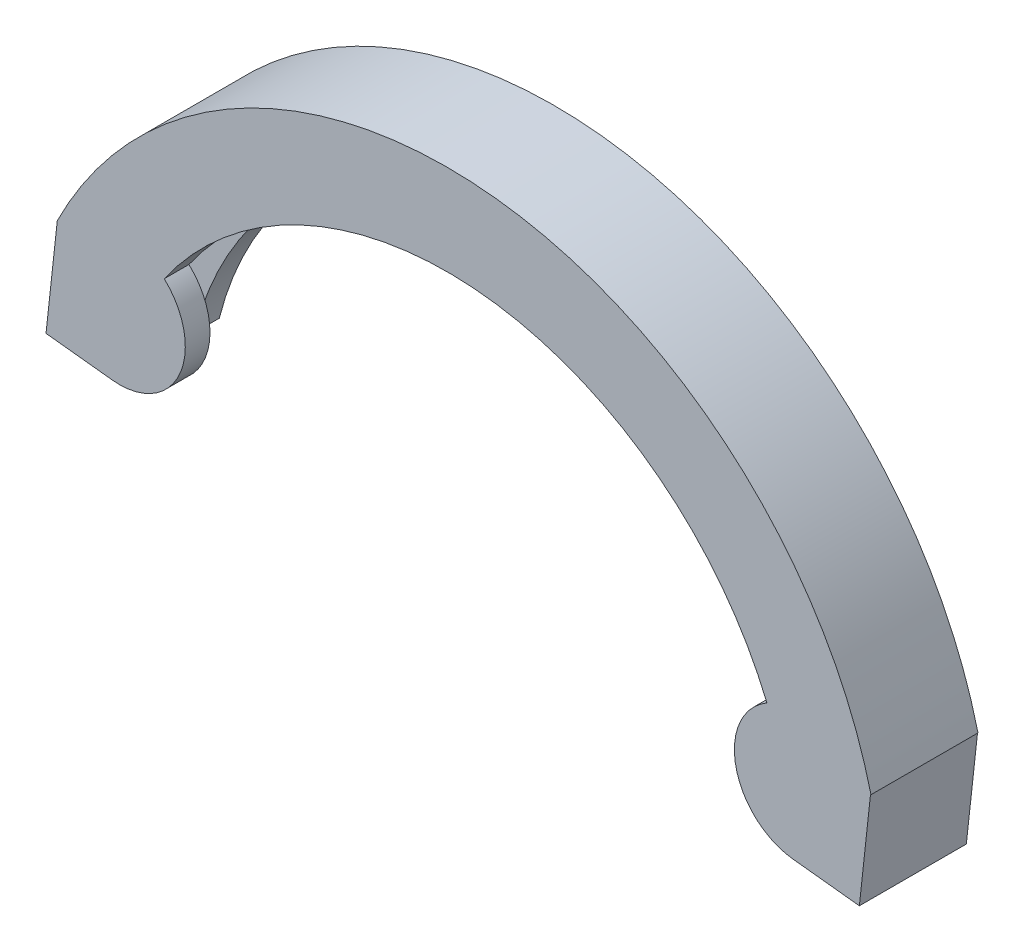
SolidWorks part; units mm, degrees
ref_plane "Front Plane" through (0, 0, 0) normal (0, 0, 1) x (1, 0, 0)
ref_plane "Top Plane" through (0, 0, 0) normal (0, 1, 0) x (1, 0, 0)
ref_plane "Right Plane" through (0, 0, 0) normal (1, 0, 0) x (0, 0, -1)
sketch "Sketch1" plane through (0, 0, 0) normal (0, 1, 0) x (1, 0, 0)
  line L1 (0, 0) -> (50, 0)
  line L2 (0, 0) -> (0, 7)
  line L3 (0, 7) -> (50, 7)
  line L4 (50, 0) -> (50, 7)
revolve "Revolve5" add sketch "Sketch1" angle 167.5 about L2
sketch "Sketch8" plane through (0, 0, 0) normal (0, 0, 1) x (1, 0, 0)
  line L0 (-48.8148, 10.822) -> (50, 0) construction
sketch "Sketch9" plane through (0, 0, -7) normal (0, 0, -1) x (-1, 0, 0)
  line L0 (-50, 0) -> (48.8148, 10.822) construction
shell "Shell2" thickness 3
sketch "Sketch11" plane through (0, 0, 3) normal (0, 0, 1) x (1, 0, 0)
  line L0 (-51.7437, 11.4713) -> (53, 0)
extrude "Cut-Extrude3" cut sketch "Sketch11" against normal blind 10 and the other way through all flip side to cut contours L0
sketch "Sketch12" plane through (0, 0, -10) normal (0, 0, -1) x (-1, 0, 0)
  line L0 (-53, 0) -> (51.7437, 11.4713)
extrude "Cut-Extrude4" cut sketch "Sketch12" against normal blind 10 and the other way through all flip side to cut contours L0
sketch "Sketch13" plane through (0, 0, -10) normal (0, 0, -1) x (-1, 0, 0)
  line L0 (-50, 0) -> (48.8148, 10.822) construction
  line L1 (-50, 0) -> (-55.7837, 52.8108) construction
  line L2 (48.8148, 10.822) -> (43.0311, 63.6327) construction
  line L3 (-55.7837, 52.8108) -> (43.0311, 63.6327) construction
  line L4 (48.7792, 11.1466) -> (47.4197, 23.5606)
  line L6 (-50.0356, 0.3247) -> (-51.3951, 12.7389)
extrude "Cut-Extrude-Thin1" cut sketch "Sketch13" against normal blind 20 and the other way through all flip side to cut thin contours L4
sketch "Sketch14" plane through (0, 0, -10) normal (0, 0, -1) x (-1, 0, 0)
  line L4 (-50.0356, 0.3247) -> (-51.3941, 12.7294)
  line L5 (48.7792, 11.1466) -> (-53, 0) construction
extrude "Cut-Extrude-Thin2" cut sketch "Sketch14" against normal blind 20 and the other way through all thin contours L4 thin type one direction reverse wall 30
sketch "Sketch15" plane through (0, 0, -10) normal (0, 0, -1) x (-1, 0, 0)
  line L0 (48.7792, 11.1466) -> (47.4197, 23.5606) construction
  line L1 (48.7792, 11.1466) -> (-50.0356, 0.3247) construction
  arc A0 (-50.0356, 0.3247) -> (48.7792, 11.1466) centre (0, 0) cw construction
  arc A1 (-41.9827, 1.2066) -> (40.7264, 10.2647) centre (0, 0) cw
extrude "Cut-Extrude-Thin3" cut sketch "Sketch15" against normal blind 20 and the other way through all thin contours A1
sketch "Sketch18" plane through (0, 0, 3) normal (0, 0, 1) x (1, 0, 0)
  line L0 (-40.7264, 10.2647) -> (41.9827, 1.2066) construction
  line L1 (-40.7264, 10.2647) -> (-39.8554, 18.2172) construction
  line L2 (41.9827, 1.2066) -> (42.8536, 9.159) construction
  line L3 (-39.8554, 18.2172) -> (42.8536, 9.159) construction
  circle A4 centre (-39.8554, 18.2172) radius 8
  circle A6 centre (42.8536, 9.159) radius 8
extrude "Boss-Extrude3" add sketch "Sketch18" against normal blind 3 contours A6 | A4
sketch "Sketch21" plane through (0, 0, 3) normal (0, 0, 1) x (1, 0, 0)
  line L0 (-40.7264, 10.2647) -> (41.9827, 1.2066) construction
  line L1 (-40.7264, 10.2647) -> (-39.8641, 18.1381) construction
  line L2 (41.9827, 1.2066) -> (42.8449, 9.08) construction
  line L3 (-39.8641, 18.1381) -> (42.8449, 9.08) construction
  circle A0 centre (-40, 18.2) radius 8 construction
  circle A1 centre (42.8449, 9.08) radius 8.0795 construction
